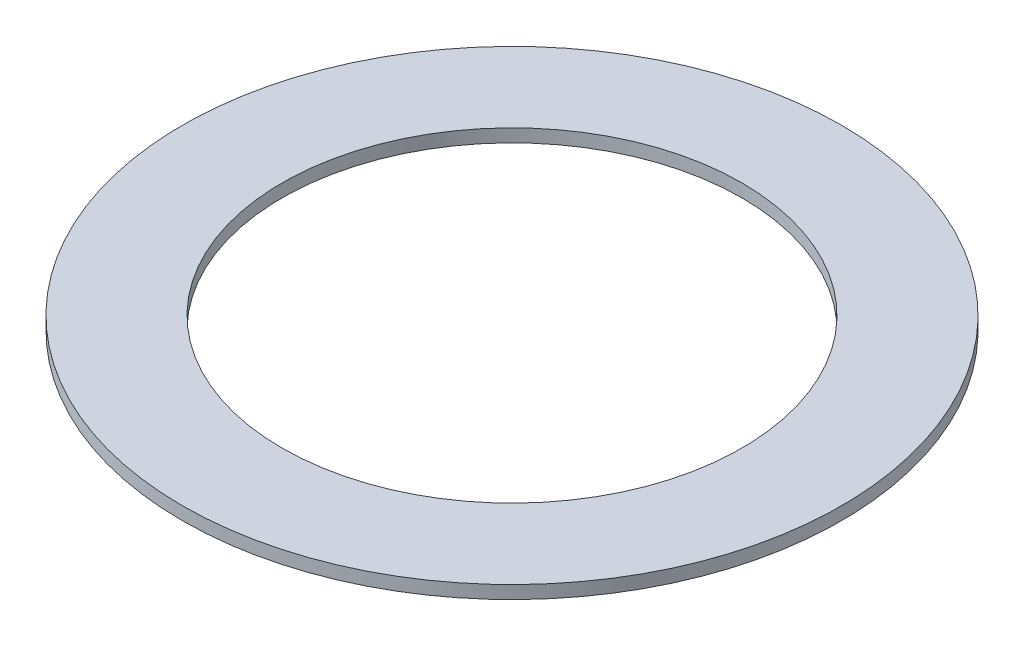
SolidWorks part; units mm, degrees
material "AISI 1020 Steel, Cold Rolled"
ref_plane "Front Plane" through (0, 0, 0) normal (0, 0, 1) x (1, 0, 0)
ref_plane "Top Plane" through (0, 0, 0) normal (0, 1, 0) x (1, 0, 0)
ref_plane "Right Plane" through (0, 0, 0) normal (1, 0, 0) x (0, 0, -1)
sketch "Sketch1" plane through (0, 0, 0) normal (0, 1, 0) x (1, 0, 0)
  circle A0 centre (0, 0) radius 5.3
  circle A1 centre (0, 0) radius 7.6
  dimension "D1" = 10.6
  dimension "D2" = 15.2
extrude "Boss-Extrude1" add sketch "Sketch1" along normal blind 0.3
